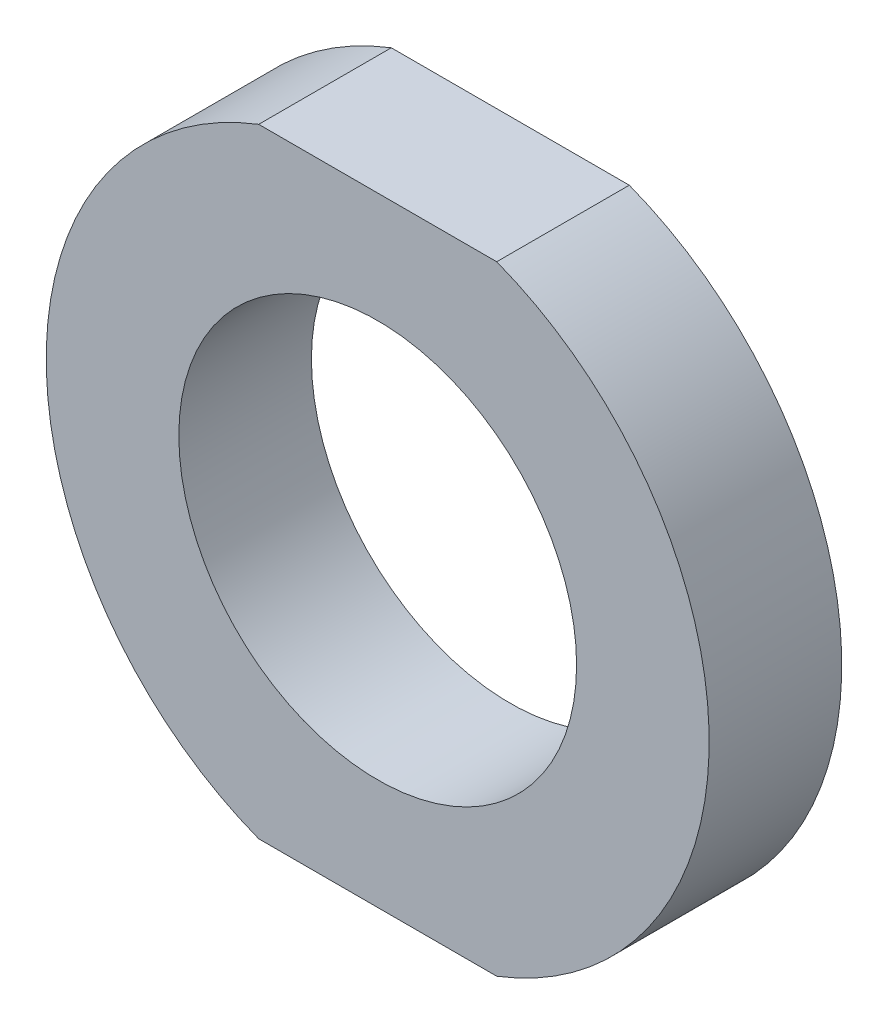
SolidWorks part; units mm, degrees
ref_plane "前视基准面" through (0, 0, 0) normal (0, 0, 1) x (1, 0, 0)
ref_plane "上视基准面" through (0, 0, 0) normal (0, 1, 0) x (1, 0, 0)
ref_plane "右视基准面" through (0, 0, 0) normal (1, 0, 0) x (0, 0, -1)
sketch "草图1" plane through (0, 0, 0) normal (0, 0, 1) x (1, 0, 0)
  line L0 (0, 0) -> (16.7135, 0) construction
  line L1 (-2.6926, 7) -> (2.6926, 7)
  line L3 (-2.6926, -7) -> (2.6926, -7)
  circle A0 centre (0, 0) radius 4.5
  arc A1 (-2.6926, 7) -> (-2.6926, -7) centre (0, 0) ccw
  arc A2 (2.6926, -7) -> (2.6926, 7) centre (0, 0) ccw
  dimension "D1" = 9
  dimension "D2" = 15
  dimension "D3" = 14
extrude "凸台-拉伸1" add sketch "草图1" along normal blind 3
cosmetic thread "装饰螺纹线3"
